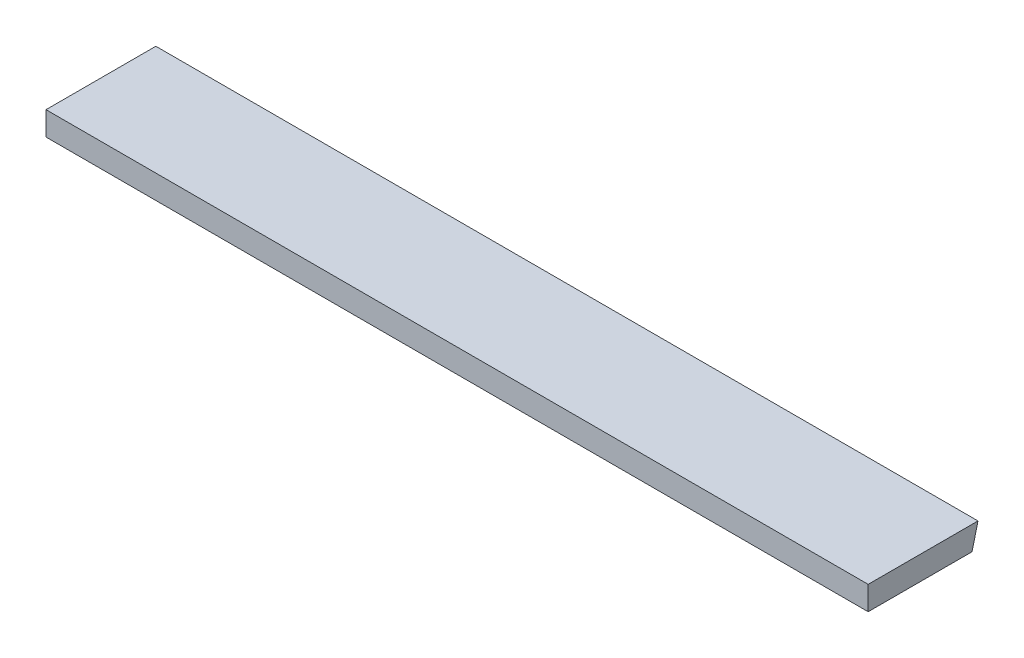
SolidWorks part; units mm, degrees
ref_plane "Front Plane" through (0, 0, 0) normal (0, 0, 1) x (1, 0, 0)
ref_plane "Top Plane" through (0, 0, 0) normal (0, 1, 0) x (1, 0, 0)
ref_plane "Right Plane" through (0, 0, 0) normal (1, 0, 0) x (0, 0, -1)
sketch "Sketch1" plane through (0, 0, 0) normal (0, 1, 0) x (1, 0, 0)
  line L0 (-93.273, 5.1913) -> (183.727, 5.1913)
  line L1 (-93.273, 5.1913) -> (-93.273, 40.1913)
  line L2 (-93.273, 40.1913) -> (183.727, 40.1913)
  line L3 (183.727, 40.1913) -> (183.727, 5.1913)
extrude "Boss-Extrude1" add sketch "Sketch1" along normal blind 8
sketch "Sketch2" plane through (-93.273, 0, 0) normal (-1, 0, 0) x (0, 0, 1)
  line L0 (-40.1913, 0) -> (-42.1963, 8)
  line L3 (-40.1913, 8) -> (-40.1913, 0) construction
  line L4 (-40.1913, 8) -> (-42.1963, 8)
  line L5 (-40.1913, 8) -> (-40.1913, 0)
  dimension "D1" = 14.07
extrude "Boss-Extrude2" add sketch "Sketch2" against normal blind 277
